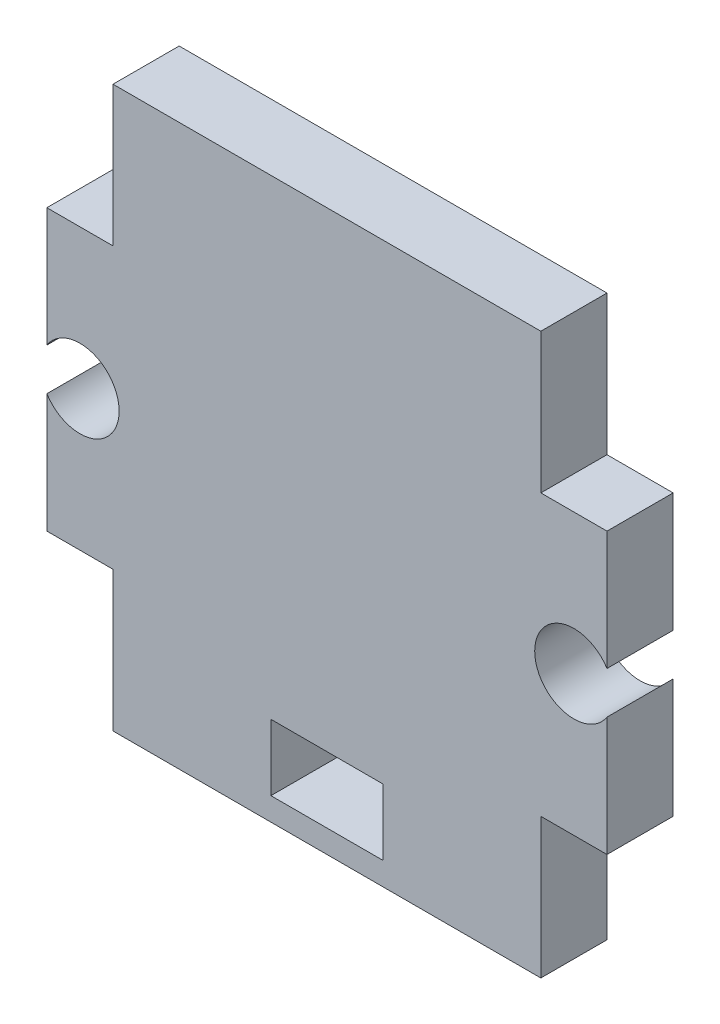
SolidWorks part; units mm, degrees
ref_plane "Front Plane" through (0, 0, 0) normal (0, 0, 1) x (1, 0, 0)
ref_plane "Top Plane" through (0, 0, 0) normal (0, 1, 0) x (1, 0, 0)
ref_plane "Right Plane" through (0, 0, 0) normal (1, 0, 0) x (0, 0, -1)
sketch "Sketch1" plane through (0, 0, 0) normal (0, 0, 1) x (1, 0, 0)
  line L1 (-12.7, -12.7) -> (12.7, -12.7)
  line L2 (-12.7, -12.7) -> (-12.7, 12.7)
  line L3 (-12.7, 12.7) -> (12.7, 12.7)
  line L4 (12.7, -12.7) -> (12.7, 12.7)
  line L5 (-12.7, -12.7) -> (12.7, 12.7) construction
  line L6 (-12.7, 12.7) -> (12.7, -12.7) construction
  point P0 (0, 0)
  dimension "D1" = 25.4
  dimension "D2" = 25.4
extrude "Boss-Extrude1" add sketch "Sketch1" along normal blind 3
sketch "Sketch2" plane through (0, 0, 3) normal (0, 0, 1) x (1, 0, 0)
  line L0 (12.7, 0) -> (-12.7, 0) construction
  line L1 (12.7, 12.7) -> (9.7, 12.7)
  line L2 (12.7, 12.7) -> (12.7, 6.35)
  line L3 (12.7, 6.35) -> (9.7, 6.35)
  line L4 (9.7, 12.7) -> (9.7, 6.35)
  line L5 (12.7, -12.7) -> (9.7, -12.7)
  line L6 (12.7, -12.7) -> (12.7, -6.35)
  line L7 (12.7, -6.35) -> (9.7, -6.35)
  line L8 (9.7, -12.7) -> (9.7, -6.35)
  line L9 (-12.7, 12.7) -> (-9.7, 12.7)
  line L10 (-12.7, 12.7) -> (-12.7, 6.35)
  line L11 (-12.7, 6.35) -> (-9.7, 6.35)
  line L12 (-9.7, 12.7) -> (-9.7, 6.35)
  line L13 (-12.7, -12.7) -> (-9.7, -12.7)
  line L14 (-12.7, -12.7) -> (-12.7, -6.35)
  line L15 (-12.7, -6.35) -> (-9.7, -6.35)
  line L16 (-9.7, -12.7) -> (-9.7, -6.35)
  line L17 (12.7, -12.7) -> (12.7, 12.7) construction
  line L18 (-12.7, 12.7) -> (-12.7, -12.7) construction
  line L19 (-12.7, -12.7) -> (12.7, -12.7) construction
  line L20 (-2.54, -11.66) -> (2.54, -11.66)
  line L21 (-2.54, -11.66) -> (-2.54, -8.66)
  line L22 (-2.54, -8.66) -> (2.54, -8.66)
  line L23 (2.54, -11.66) -> (2.54, -8.66)
  line L24 (-2.54, -11.66) -> (2.54, -8.66) construction
  line L25 (-2.54, -8.66) -> (2.54, -11.66) construction
  circle A0 centre (-11.2, 0) radius 1.778
  circle A1 centre (11.2, 0) radius 1.778
  point P30 (0, -10.16)
  dimension "D9" = 3.556
  dimension "D10" = 1.5
  dimension "D11" = 3.556
  dimension "D1" = 6.35
  dimension "D2" = 6.35
  dimension "D3" = 6.35
  dimension "D4" = 6.35
  dimension "D5" = 3
  dimension "D6" = 3
  dimension "D7" = 3
  dimension "D8" = 3
  dimension "D12" = 1.5
  dimension "D13" = 3
  dimension "D14" = 2.54
  dimension "D15" = 5.08
extrude "Cut-Extrude1" cut sketch "Sketch2" against normal through all
